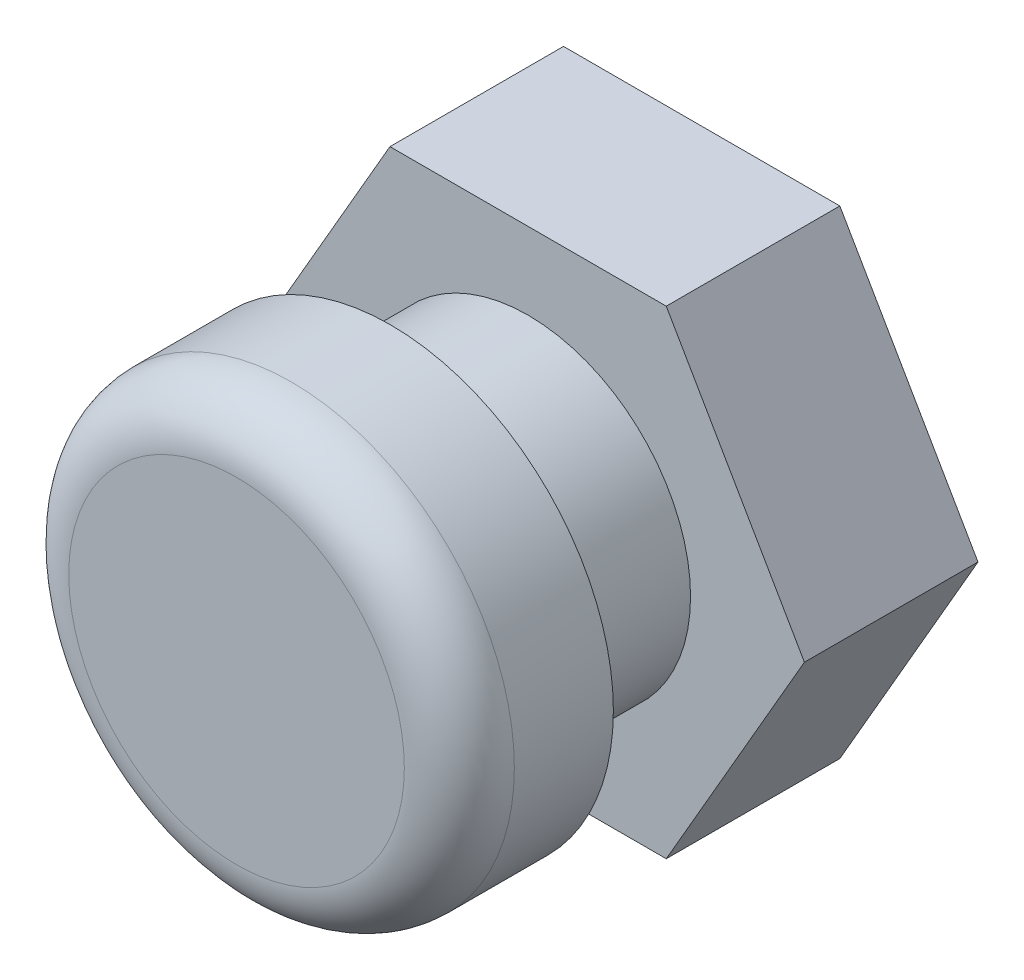
SolidWorks part; units mm, degrees
ref_plane "Front Plane" through (0, 0, 0) normal (0, 0, 1) x (1, 0, 0)
ref_plane "Top Plane" through (0, 0, 0) normal (0, 1, 0) x (1, 0, 0)
ref_plane "Right Plane" through (0, 0, 0) normal (1, 0, 0) x (0, 0, -1)
ref_plane "Plane1" through (0, 0, 0) normal (0, 0, 1) x (1, 0, 0)
sketch "Sketch1" plane through (0, 0, 0) normal (0, 0, 1) x (1, 0, 0)
  circle A0 centre (0, 0) radius 5.1435
extrude "Extrude1" add sketch "Sketch1" along normal blind 3.556
sketch "Sketch2" plane through (0, 0, 0) normal (0, 0, -1) x (-1, 0, 0)
  circle A0 centre (0, 0) radius 3.75
extrude "Extrude2" add sketch "Sketch2" along normal blind 3.175
sketch "Sketch3" plane through (0, 0, -3.175) normal (0, 0, -1) x (-1, 0, 0)
  line L0 (-3.1896, -5.5245) -> (3.1896, -5.5245)
  line L1 (3.1896, -5.5245) -> (6.3791, 0)
  line L2 (6.3791, 0) -> (3.1896, 5.5245)
  line L3 (3.1896, 5.5245) -> (-3.1896, 5.5245)
  line L4 (-3.1896, 5.5245) -> (-6.3791, 0)
  line L5 (-6.3791, 0) -> (-3.1896, -5.5245)
  line L6 (-7.0171, 0) -> (7.0171, 0) construction
  dimension "D1" = 11.049
extrude "Extrude3" add sketch "Sketch3" along normal blind 4.0074
fillet "Fillet1" radius 1.27 1 edges at (5.1435, 0, 3.556)
